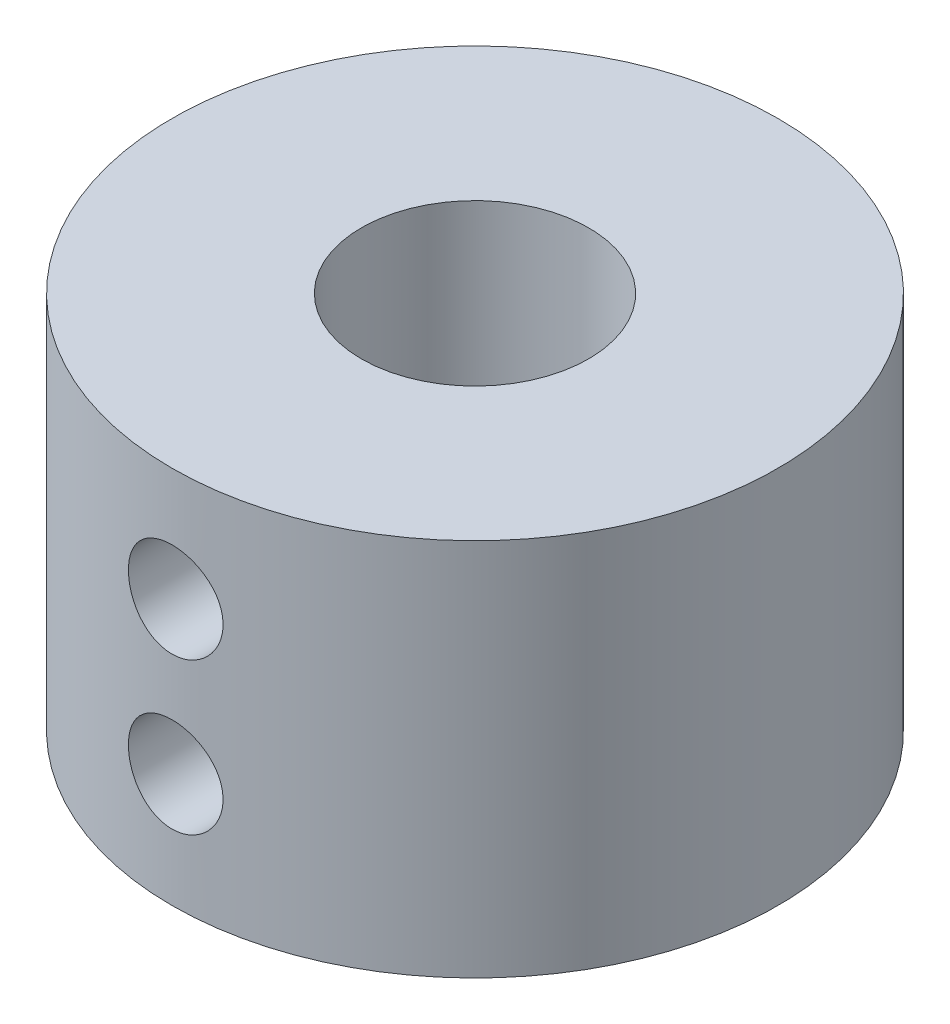
SolidWorks part; units mm, degrees
ref_plane "Front Plane" through (0, 0, 0) normal (0, 0, 1) x (1, 0, 0)
ref_plane "Top Plane" through (0, 0, 0) normal (0, 1, 0) x (1, 0, 0)
ref_plane "Right Plane" through (0, 0, 0) normal (1, 0, 0) x (0, 0, -1)
sketch "Sketch1" plane through (0, 0, 0) normal (0, 1, 0) x (1, 0, 0)
  circle A0 centre (0, 0) radius 12.7
  dimension "D1" = 25.4
extrude "Boss-Extrude1" add sketch "Sketch1" along normal blind 15.875
sketch "Sketch2" plane through (0, 15.875, 0) normal (0, 1, 0) x (1, 0, 0)
  circle A0 centre (0, 0) radius 4.7625
  dimension "D1" = 9.525
extrude "Cut-Extrude1" cut sketch "Sketch2" against normal through all
sketch "Sketch3" plane through (0, 0, 0) normal (0, 0, 1) x (1, 0, 0)
  line L0 (-12.7, 0) -> (12.7, 0) construction
  circle A0 centre (0, 4.7625) radius 1.9844
  circle A1 centre (0, 11.1125) radius 1.9844
  dimension "D1" = 3.9688
  dimension "D2" = 6.35
  dimension "D3" = 4.7625
extrude "Cut-Extrude2" cut sketch "Sketch3" along normal through all
